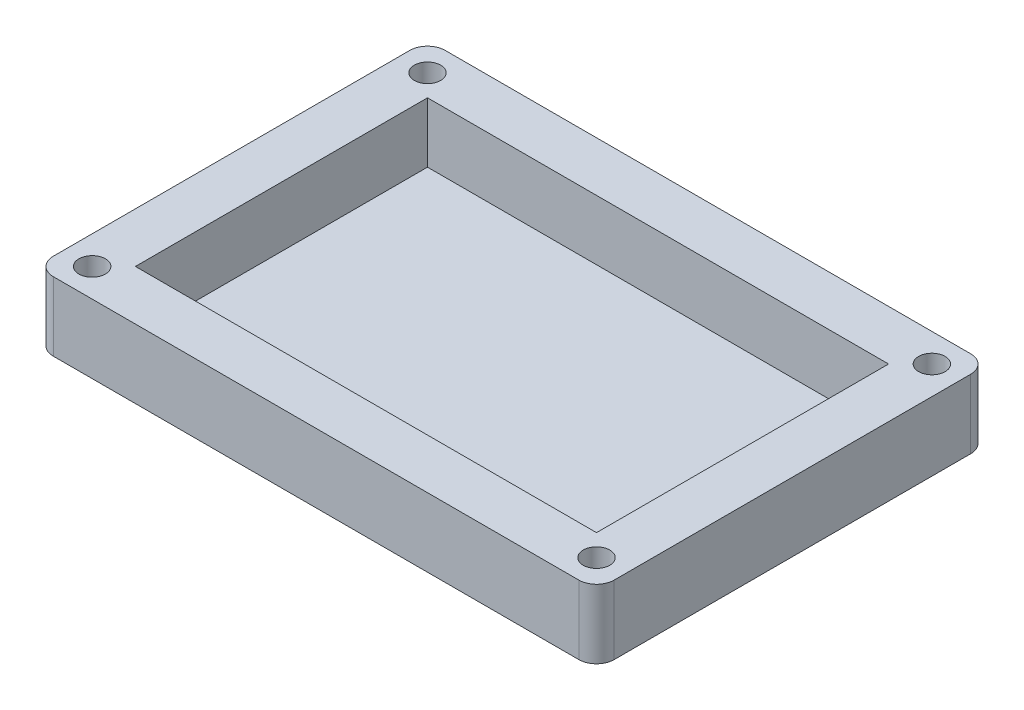
SolidWorks part; units mm, degrees
ref_plane "Front Plane" through (0, 0, 0) normal (0, 0, 1) x (1, 0, 0)
ref_plane "Top Plane" through (0, 0, 0) normal (0, 1, 0) x (1, 0, 0)
ref_plane "Right Plane" through (0, 0, 0) normal (1, 0, 0) x (0, 0, -1)
sketch "Sketch1" plane through (0, 0, 0) normal (0, 1, 0) x (1, 0, 0)
  line L1 (0, 0) -> (63.5, 0)
  line L2 (0, 0) -> (0, 44.3653)
  line L3 (0, 44.3653) -> (63.5, 44.3653)
  line L4 (63.5, 0) -> (63.5, 44.3653)
  dimension "D1" = 63.5
  dimension "D2" = 44.3653
extrude "Boss-Extrude1" add sketch "Sketch1" along normal blind 7.8
sketch "Sketch2" plane through (0, 7.8, 0) normal (0, 1, 0) x (1, 0, 0)
  line L0 (0, 44.3653) -> (0, 0) construction
  line L1 (5.65, 5.65) -> (57.85, 5.65)
  line L2 (5.65, 5.65) -> (5.65, 38.7153)
  line L3 (5.65, 38.7153) -> (57.85, 38.7153)
  line L4 (57.85, 5.65) -> (57.85, 38.7153)
  line L5 (63.5, 44.3653) -> (0, 44.3653) construction
  line L7 (63.5, 0) -> (63.5, 44.3653) construction
  line L8 (0, 0) -> (63.5, 0) construction
  dimension "D1" = 5.65
  dimension "D2" = 5.65
  dimension "D3" = 5.65
  dimension "D4" = 5.65
extrude "Cut-Extrude1" cut sketch "Sketch2" against normal blind 6.8
sketch "Sketch3" plane through (0, 7.8, 0) normal (0, 1, 0) x (1, 0, 0)
  line L0 (63.5, 44.3653) -> (0, 44.3653) construction
  line L1 (0, 44.3653) -> (0, 0) construction
  line L2 (63.5, 0) -> (63.5, 44.3653) construction
  line L3 (0, 0) -> (63.5, 0) construction
  circle A0 centre (3.2, 3.2) radius 1.5
  circle A1 centre (3.2, 41.1653) radius 1.5
  circle A2 centre (60.3, 41.1653) radius 1.5
  circle A3 centre (60.3, 3.2) radius 1.5
  dimension "D1" = 3
  dimension "D2" = 3.2
  dimension "D3" = 3.2
  dimension "D4" = 3.2
  dimension "D5" = 3.2
  dimension "D6" = 3.2
  dimension "D7" = 3.2
  dimension "D8" = 3.2
  dimension "D9" = 3.2
extrude "Cut-Extrude2" cut sketch "Sketch3" against normal blind 7.5
fillet "Fillet1" radius 2 4 edges at (0, 3.9, -44.3653) (63.5, 3.9, -44.3653) (63.5, 3.9, 0) (0, 3.9, 0)
